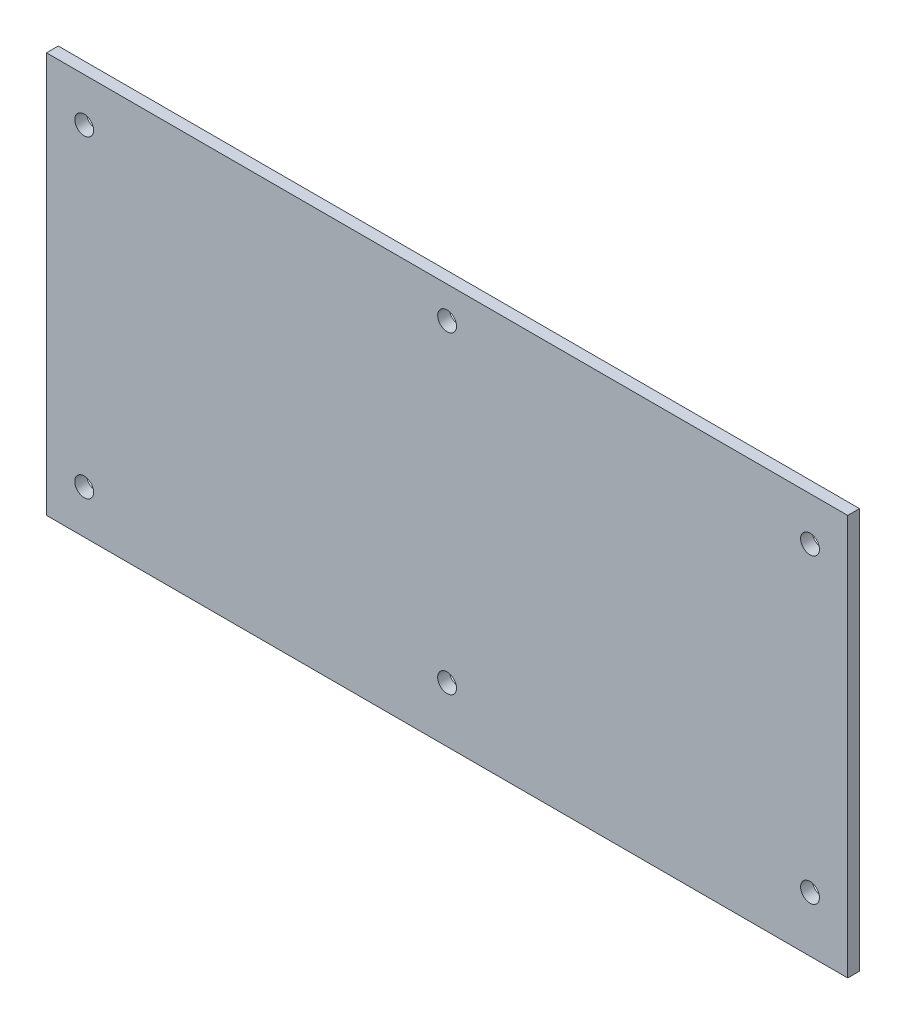
SolidWorks part; units mm, degrees
material "ASTM A36 Steel"
ref_plane "Front Plane" through (0, 0, 0) normal (0, 0, 1) x (1, 0, 0)
ref_plane "Top Plane" through (0, 0, 0) normal (0, 1, 0) x (1, 0, 0)
ref_plane "Right Plane" through (0, 0, 0) normal (1, 0, 0) x (0, 0, -1)
sketch "Sketch1" plane through (0, 0, 0) normal (0, 0, 1) x (1, 0, 0)
  line L1 (137.1349, 48.2341) -> (-202.8651, 48.2341)
  line L2 (137.1349, 48.2341) -> (137.1349, -121.7659)
  line L3 (137.1349, -121.7659) -> (-202.8651, -121.7659)
  line L4 (-202.8651, 48.2341) -> (-202.8651, -121.7659)
  circle A0 centre (121.1349, 29.7341) radius 4
  circle A1 centre (-32.8651, 34.7341) radius 4
  circle A2 centre (-186.8651, 29.7341) radius 4
  circle A3 centre (-186.8651, -103.2659) radius 4
  circle A4 centre (-32.8651, -98.2659) radius 4
  circle A5 centre (121.1349, -98.2659) radius 4
  dimension "D7" = 8
  dimension "D8" = 8
  dimension "D9" = 8
  dimension "D10" = 8
  dimension "D11" = 8
  dimension "D12" = 8
  dimension "D5" = 18.5
  dimension "D1" = 340
  dimension "D2" = 170
  dimension "D3" = 133
  dimension "D4" = 308
extrude "Boss-Extrude1" add sketch "Sketch1" along normal blind 5
